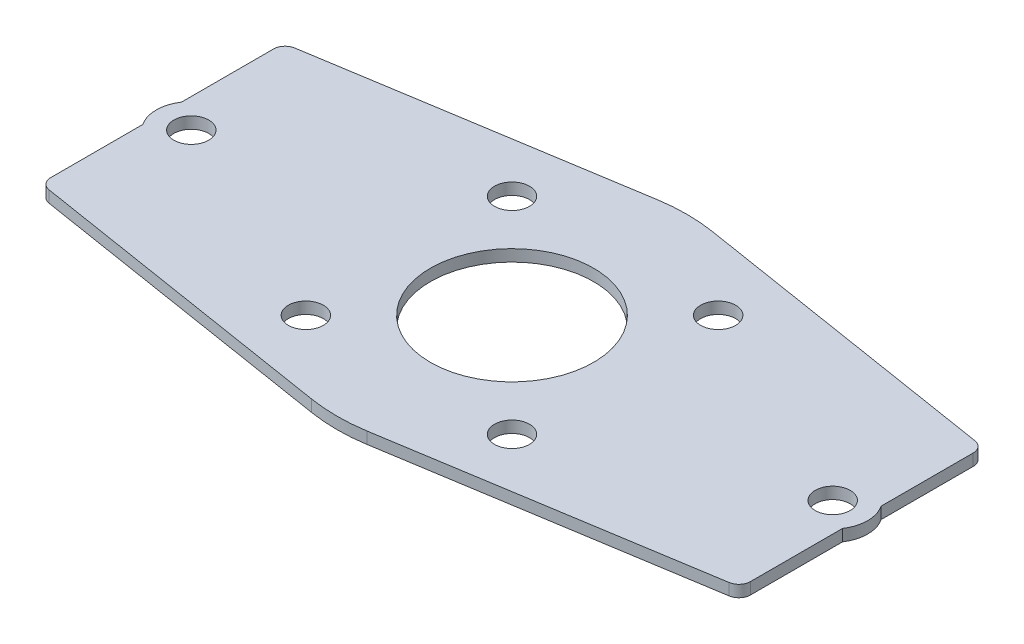
SolidWorks part; units mm, degrees
material "Hexcel AS4C (3000 Filaments)"
ref_plane "Front Plane" through (0, 0, 0) normal (0, 0, 1) x (1, 0, 0)
ref_plane "Top Plane" through (0, 0, 0) normal (0, 1, 0) x (1, 0, 0)
ref_plane "Right Plane" through (0, 0, 0) normal (1, 0, 0) x (0, 0, -1)
sketch "Sketch1" plane through (0, 0, 0) normal (0, 1, 0) x (1, 0, 0)
  line L12 (-29.1577, 10.5337) -> (-2.3654, 14.8123)
  line L13 (-30, 9.5463) -> (-30, -9.5463)
  line L14 (30, 9.5463) -> (30, -9.5463)
  line L16 (-29.1577, -10.5337) -> (-2.3654, -14.8123)
  line L17 (29.1577, -10.5337) -> (2.3654, -14.8123)
  line L18 (29.1577, 10.5337) -> (2.3654, 14.8123)
  circle A1 centre (-8.8388, 8.8388) radius 1.5
  circle A2 centre (8.8388, 8.8388) radius 1.5
  circle A3 centre (8.8388, -8.8388) radius 1.5
  circle A4 centre (-8.8388, -8.8388) radius 1.5
  circle A6 centre (-27.5, 0) radius 1.5
  circle A7 centre (27.5, 0) radius 1.5
  circle A18 centre (0, 0) radius 7
  circle A19 centre (0, 0) radius 15
  circle A20 centre (-27.5, 0) radius 3
  circle A21 centre (27.5, 0) radius 3
  arc A22 (-29.1577, 10.5337) -> (-30, 9.5463) centre (-29, 9.5463) ccw
  arc A23 (-30, -9.5463) -> (-29.1577, -10.5337) centre (-29, -9.5463) ccw
  arc A24 (29.1577, 10.5337) -> (30, 9.5463) centre (29, 9.5463) cw
  arc A25 (30, -9.5463) -> (29.1577, -10.5337) centre (29, -9.5463) cw
  point P14 (0, 0)
  point P16 (0, 0)
  point P20 (0, 0)
  point P26 (0, 0)
  point P29 (0, 0)
  dimension "D1" = 4
  dimension "D2" = 1
extrude "Boss-Extrude1" add sketch "Sketch1" along normal blind 1 contours A19 A1 A2 A3 A4 A18 | A21 L14 L18 A19 L17 | L14 A21 A7 | A20 L13 L16 A19 L12 | L13 A20 A6 | L13 A20 | L14 A21
